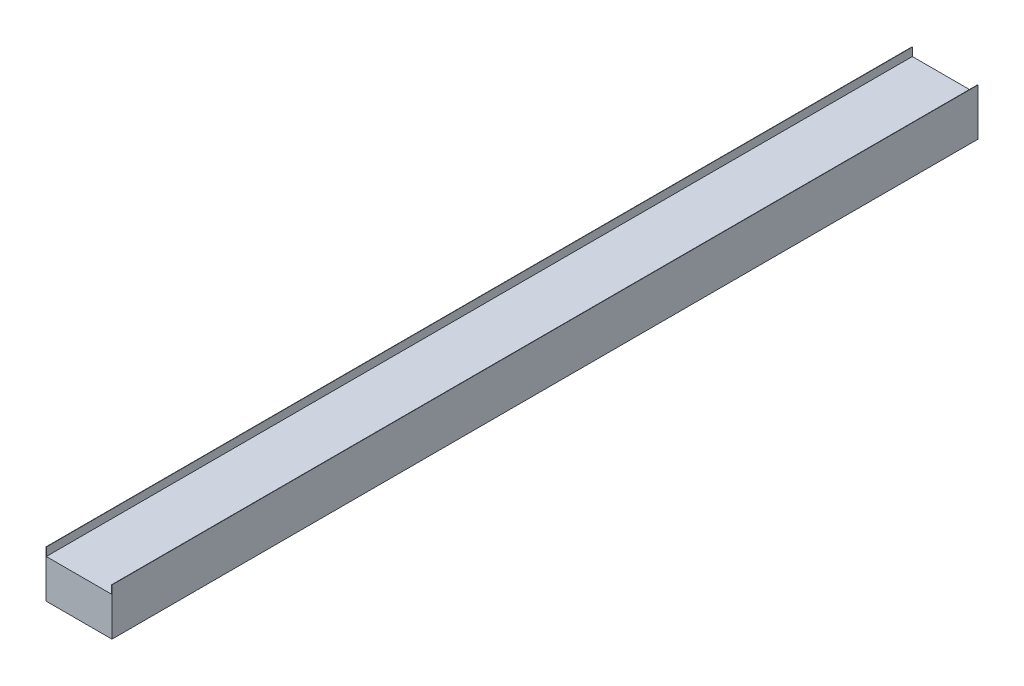
SolidWorks part; units mm, degrees
ref_plane "Alzado" through (0, 0, 0) normal (0, 0, 1) x (1, 0, 0)
ref_plane "Planta" through (0, 0, 0) normal (0, 1, 0) x (1, 0, 0)
ref_plane "Vista lateral" through (0, 0, 0) normal (1, 0, 0) x (0, 0, -1)
sketch "Croquis1" plane through (0, 0, 0) normal (0, 0, 1) x (1, 0, 0)
  line L0 (4, 0) -> (4, -100)
  line L1 (0, 0) -> (4, 0)
  line L2 (0, 0) -> (0, -570)
  line L3 (0, -570) -> (800, -570)
  line L4 (800, 0) -> (800, -570)
  line L5 (4, -100) -> (796, -100)
  line L6 (796, -100) -> (796, 0)
  line L7 (796, 0) -> (800, 0)
  dimension "D1" = 800
  dimension "D2" = 570
  dimension "D3" = 4
  dimension "D4" = 100
  dimension "D5" = 4
extrude "Saliente-Extruir1" add sketch "Croquis1" along normal blind 10500
